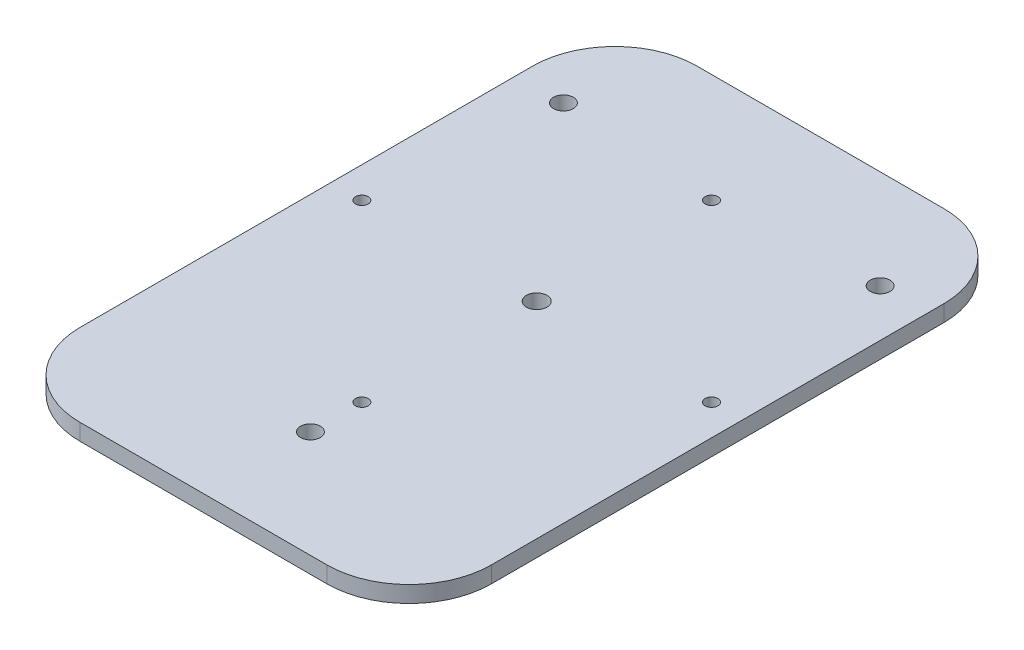
SolidWorks part; units mm, degrees
ref_plane "Plano frontal" through (0, 0, 0) normal (0, 0, 1) x (1, 0, 0)
ref_plane "Plano superior" through (0, 0, 0) normal (0, 1, 0) x (1, 0, 0)
ref_plane "Plano direito" through (0, 0, 0) normal (1, 0, 0) x (0, 0, -1)
sketch "Esboço1" plane through (0, 0, 0) normal (0, 1, 0) x (1, 0, 0)
  line L0 (-30.3812, -73.8564) -> (29.6188, -73.8564)
  line L1 (-50.3812, -53.8564) -> (-50.3812, 56.1436)
  line L2 (-30.3812, 76.1436) -> (29.6188, 76.1436)
  line L3 (49.6188, -53.8564) -> (49.6188, 56.1436)
  line L4 (-50.3812, -73.8564) -> (49.6188, 76.1436) construction
  line L5 (-50.3812, 76.1436) -> (49.6188, -73.8564) construction
  line L6 (-0.3812, 1.1436) -> (-0.3812, 49.6436) construction
  line L7 (-0.3812, 1.1436) -> (-0.3812, 7.1436) construction
  line L8 (-0.3812, 7.1436) -> (-42.8812, 7.1436) construction
  line L9 (-0.3812, 7.1436) -> (42.1188, 7.1436) construction
  line L10 (-0.3812, 7.1436) -> (-0.3812, -35.3564) construction
  arc A0 (29.6188, -73.8564) -> (49.6188, -53.8564) centre (29.6188, -53.8564) ccw
  arc A1 (-30.3812, -73.8564) -> (-50.3812, -53.8564) centre (-30.3812, -53.8564) cw
  arc A2 (49.6188, 56.1436) -> (29.6188, 76.1436) centre (29.6188, 56.1436) ccw
  arc A3 (-50.3812, 56.1436) -> (-30.3812, 76.1436) centre (-30.3812, 56.1436) cw
  circle A4 centre (-0.3812, 7.1436) radius 2.5
  circle A5 centre (38.1188, 52.1436) radius 2.4
  circle A6 centre (-38.8812, 52.1436) radius 2.4
  circle A7 centre (-0.3812, -47.8564) radius 2.4
  circle A8 centre (-42.8812, 7.1436) radius 1.55
  circle A9 centre (42.1188, 7.1436) radius 1.55
  circle A10 centre (-0.3812, -47.8564) radius 2.4
  circle A11 centre (-0.3812, -35.3564) radius 1.55
  circle A12 centre (-0.3812, 7.1436) radius 42.5 construction
  circle A13 centre (-0.3812, 49.6436) radius 1.55
  circle A14 centre (-0.3812, -35.3564) radius 5.5 construction
  circle A15 centre (-0.3812, -47.8564) radius 4.5 construction
  point P0 (-0.3812, 1.1436)
  point P39 (-0.3812, 1.1436)
  point P42 (-0.3812, 1.1436)
  dimension "D1" = 20
  dimension "D2" = 5
  dimension "D3" = 4.8
  dimension "D4" = 4.8
  dimension "D5" = 42.5
  dimension "D7" = 3.1
  dimension "D12" = 9
  dimension "D13" = 48.5
  dimension "D6" = 3.1
  dimension "D8" = 3.1
  dimension "D14" = 3.1
  dimension "D11" = 11
  dimension "D9" = 42.5
  dimension "D10" = 42.5
  dimension "D15" = 6
extrude "Ressalto-extrusão1" add sketch "Esboço1" along normal blind 4
